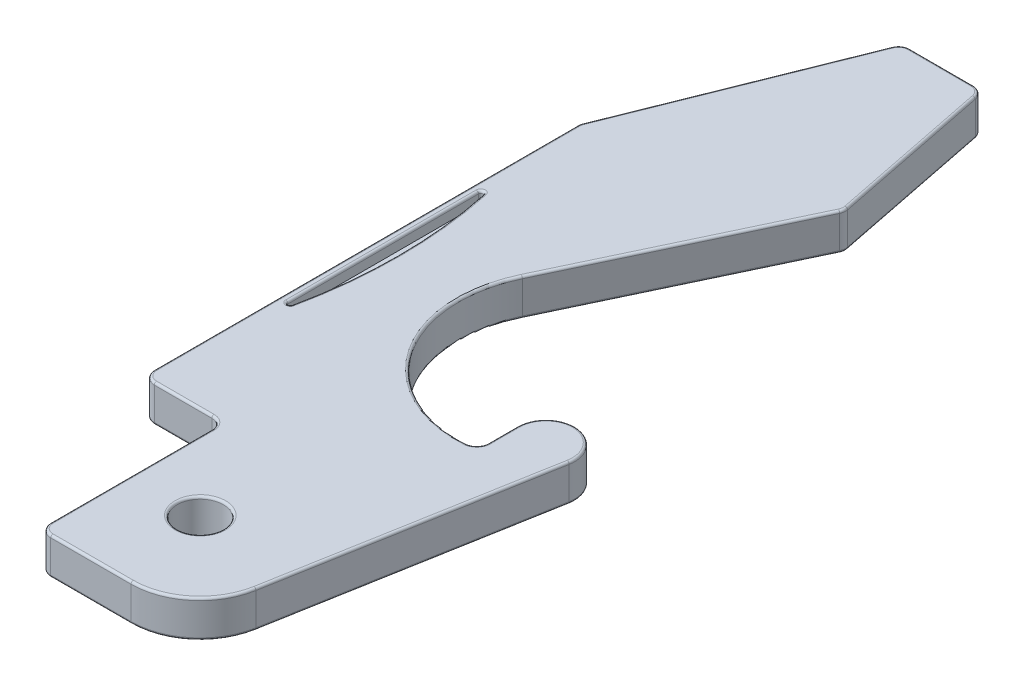
SolidWorks part; units mm, degrees
ref_plane "Front Plane" through (0, 0, 0) normal (0, 0, 1) x (1, 0, 0)
ref_plane "Top Plane" through (0, 0, 0) normal (0, 1, 0) x (1, 0, 0)
ref_plane "Right Plane" through (0, 0, 0) normal (1, 0, 0) x (0, 0, -1)
sketch "Sketch1" plane through (0, 0, 0) normal (0, 1, 0) x (1, 0, 0)
  line L0 (0, 0) -> (0, 37) construction
  line L1 (0, 37) -> (12.5, 37) construction
  line L2 (12.5, 37) -> (12.5, 0) construction
  line L3 (12.5, 0) -> (0, 0) construction
  line L4 (0, 0) -> (0, 27)
  line L5 (0, 27) -> (4, 37)
  line L6 (4, 37) -> (7.5, 37)
  line L7 (7.5, 37) -> (9, 29.5)
  line L8 (9, 29.5) -> (4.4969, 20)
  line L9 (10.0194, 12.5436) -> (10.0194, 14.25)
  line L10 (12.5, 14.0307) -> (10, 0)
  line L11 (10, 0) -> (0, 0)
  arc A0 (4.4969, 20) -> (10.0194, 12.5436) centre (9.25, 17.747) ccw
  arc A1 (10.0194, 14.25) -> (12.5, 14.0307) centre (11.2694, 14.25) cw
  point P15 (7.22, 13.1191)
  dimension "D10" = 1.25
  dimension "D11" = 5.26
  dimension "D1" = 37
  dimension "D2" = 12.5
  dimension "D3" = 10
  dimension "D4" = 3.5
  dimension "D5" = 4
  dimension "D6" = 10
  dimension "D7" = 7.5
  dimension "D8" = 9.5
  dimension "D9" = 22.75
  dimension "D12" = 9.25
  dimension "D13" = 9
extrude "Boss-Extrude1" add sketch "Sketch1" along normal blind 1.6
fillet "Fillet1" radius 3 1 edges at (10, 0.8, 0)
sketch "Sketch2" plane through (0, 1.6, 0) normal (0, 1, 0) x (1, 0, 0)
  line L0 (0, 0) -> (7.4873, 0) construction
  line L1 (0, 0) -> (3.5, 0)
  line L2 (0, 0) -> (0, 8)
  line L3 (0, 8) -> (3.5, 8)
  line L4 (3.5, 0) -> (3.5, 8)
  circle A0 centre (6.5, 4) radius 1
  dimension "D3" = 2
  dimension "D1" = 8
  dimension "D2" = 3.5
  dimension "D4" = 4
  dimension "D5" = 3
extrude "Cut-Extrude1" cut sketch "Sketch2" against normal through all
fillet "Fillet2" radius 0.5 8 edges at (10.0194, 0.8, -12.5436) (9, 0.8, -29.5) (7.5, 0.8, -37) (4, 0.8, -37) (0, 0.8, -27) (3.5, 0.8, -8) (0, 0.8, -8) (3.5, 0.8, 0)
fillet "Fillet3" radius 0.1 44 edges at (7.4071, 0, -36.8867) (5.7143, 0, -37) (4.0582, 0, -36.914) (1.955, 0, -31.8875) (0.009, 0, -26.9983) (0, 0, -17.7019) (0.1464, 0, -8.1464) (1.75, 0, -8) (3.3536, 0, -7.8536) (3.5, 0, -4) (3.6464, 0, -0.1464) (5.7436, 0, 0) (9.4136, 0, -0.7001) (11.4704, 0, -8.2522) (11.3794, 0, -15.4951) (10.0194, 0, -13.6223) (9.8828, 0, -12.6512) (4.8863, 0, -14.8101) (6.713, 0, -24.6751) (8.9735, 0, -29.5033) (8.2739, 0, -33.1303) (6.5, 0, -3) (6.5, 1.6, -3) (4.8863, 1.6, -14.8101) (9.8828, 1.6, -12.6512) (10.0194, 1.6, -13.6223) (11.3794, 1.6, -15.4951) (11.4704, 1.6, -8.2522) (9.4136, 1.6, -0.7001) (5.7436, 1.6, 0) (3.6464, 1.6, -0.1464) (3.5, 1.6, -4) (3.3536, 1.6, -7.8536) (1.75, 1.6, -8) (0.1464, 1.6, -8.1464) (0, 1.6, -17.7019) (0.009, 1.6, -26.9983) (1.955, 1.6, -31.8875) (4.0582, 1.6, -36.914) (5.7143, 1.6, -37) (7.4071, 1.6, -36.8867) (8.2739, 1.6, -33.1303) (8.9735, 1.6, -29.5033) (6.713, 1.6, -24.6751)
sketch "Sketch3" plane through (0, 1.6, 0) normal (0, 1, 0) x (1, 0, 0)
  line L0 (0.35, 23.1) -> (0.35, 13.1)
  line L1 (0.1, 26.9037) -> (0.1, 8.5) construction
  arc A0 (0.35, 23.1) -> (0.35, 13.1) centre (-19.0149, 18.1) cw
  dimension "D2" = 20
  dimension "D1" = 10
  dimension "D3" = 0.25
  dimension "D4" = 5
extrude "Cut-Extrude2" cut sketch "Sketch3" against normal blind 0.5
fillet "Fillet4" radius 0.1 4 edges at (0.35, 1.6, -18.1) (0.9851, 1.6, -18.1) (0.35, 1.35, -23.1) (0.35, 1.35, -13.1)
